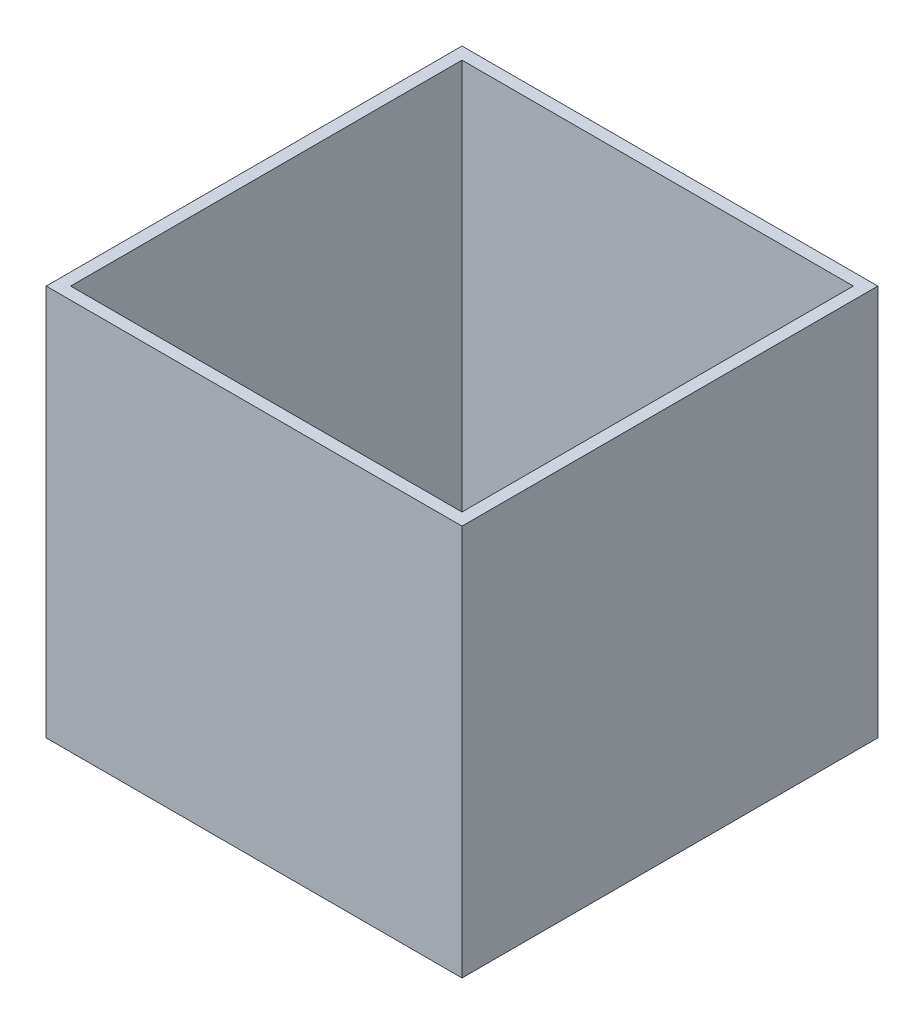
SolidWorks part; units mm, degrees
ref_plane "Front Plane" through (0, 0, 0) normal (0, 0, 1) x (1, 0, 0)
ref_plane "Top Plane" through (0, 0, 0) normal (0, 1, 0) x (1, 0, 0)
ref_plane "Right Plane" through (0, 0, 0) normal (1, 0, 0) x (0, 0, -1)
sketch "Sketch1" plane through (0, 0, 0) normal (0, 1, 0) x (1, 0, 0)
  line L1 (-101.6, 101.6) -> (101.6, 101.6)
  line L2 (-101.6, 101.6) -> (-101.6, -101.6)
  line L3 (-101.6, -101.6) -> (101.6, -101.6)
  line L4 (101.6, 101.6) -> (101.6, -101.6)
  line L5 (-107.95, 107.95) -> (107.95, 107.95)
  line L6 (-107.95, 107.95) -> (-107.95, -107.95)
  line L7 (-107.95, -107.95) -> (107.95, -107.95)
  line L8 (107.95, 107.95) -> (107.95, -107.95)
  dimension "D1" = 203.2
  dimension "D2" = 203.2
  dimension "D3" = 101.6
  dimension "D4" = 101.6
  dimension "D5" = 6.35
  dimension "D6" = 6.35
  dimension "D7" = 6.35
  dimension "D8" = 6.35
extrude "Boss-Extrude1" add sketch "Sketch1" along normal blind 203.2
sketch "Sketch3" plane through (0, 0, 107.95) normal (0, 0, 1) x (1, 0, 0)
  circle A0 centre (51.8017, 137.7493) radius 36.3678
